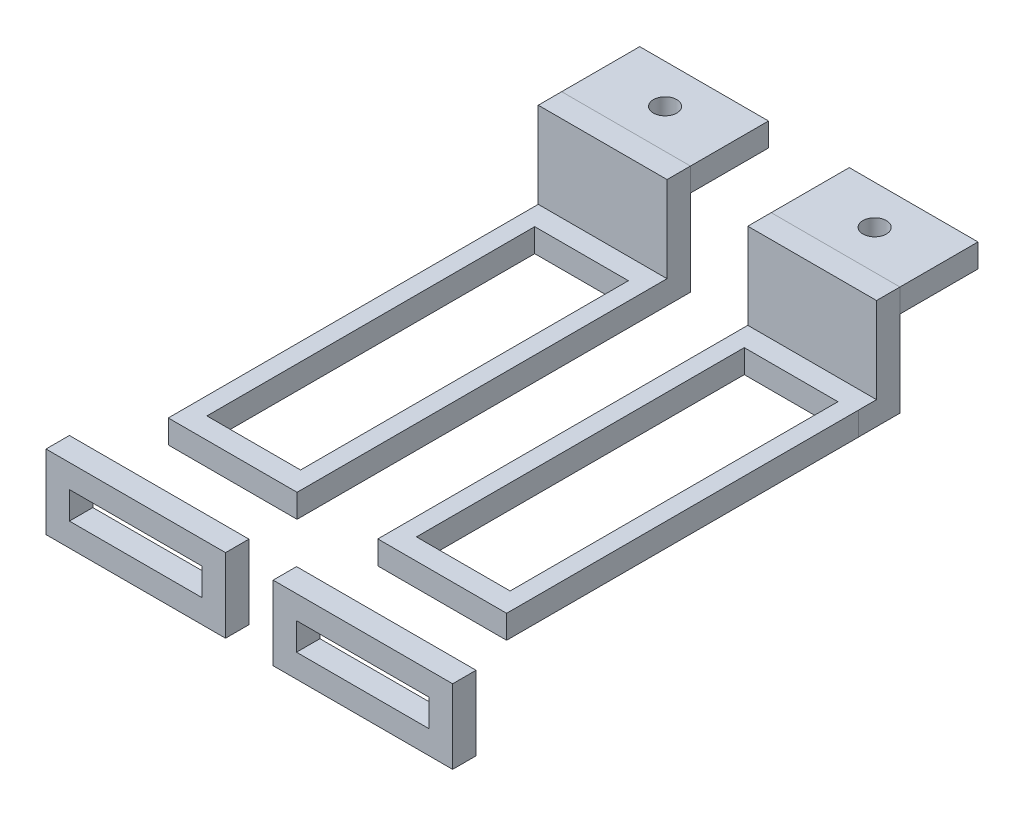
SolidWorks part; units mm, degrees
ref_plane "Front Plane" through (0, 0, 0) normal (0, 0, 1) x (1, 0, 0)
ref_plane "Top Plane" through (0, 0, 0) normal (0, 1, 0) x (1, 0, 0)
ref_plane "Right Plane" through (0, 0, 0) normal (1, 0, 0) x (0, 0, -1)
sketch "Sketch1" plane through (0, 0, 0) normal (0, 0, 1) x (1, 0, 0)
  line L1 (98.6394, -11.1578) -> (-71.3606, -11.1578)
  line L2 (98.6394, -11.1578) -> (98.6394, -8.1578)
  line L3 (98.6394, -8.1578) -> (-71.3606, -8.1578)
  line L4 (-71.3606, -11.1578) -> (-71.3606, -8.1578)
  line L5 (98.6394, -11.1578) -> (-71.3606, -8.1578) construction
  line L6 (98.6394, -8.1578) -> (-71.3606, -11.1578) construction
  point P0 (13.6394, -9.6578)
extrude "Boss-Extrude1" add sketch "Sketch1" along normal blind 10
sketch "Sketch2" plane through (0, -8.1578, 0) normal (0, 1, 0) x (1, 0, 0)
  line L0 (98.6394, -10) -> (-71.3606, -10) construction
  line L1 (-53.3606, -7) -> (-8.0606, -7)
  line L2 (-53.3606, -7) -> (-53.3606, -10)
  line L3 (-53.3606, -10) -> (-8.0606, -10)
  line L4 (-8.0606, -7) -> (-8.0606, -10)
  line L5 (-53.3606, -7) -> (-8.0606, -10) construction
  line L6 (-53.3606, -10) -> (-8.0606, -7) construction
  line L7 (-71.3606, -10) -> (-71.3606, 0) construction
  point P0 (-30.7106, -8.5)
  dimension "D1" = 0
  dimension "D2" = 18
sketch "Sketch4" plane through (0, -8.1578, 0) normal (0, 1, 0) x (1, 0, 0)
  line L0 (-71.3606, -10) -> (-71.3606, 0) construction
  line L1 (98.6394, -10) -> (98.6394, 0) construction
  circle A0 centre (-63.3606, -4.9385) radius 1.2
  circle A1 centre (90.6394, -5.2832) radius 1.2
  dimension "D1" = 8
  dimension "D2" = 8
extrude "Cut-Extrude1" cut sketch "Sketch4" against normal blind 21
extrude "Boss-Extrude6" add sketch "Sketch2" along normal blind 20.3
sketch "Sketch5" plane through (0, 0, 7) normal (0, 0, -1) x (-1, 0, 0)
  line L0 (8.0606, 12.1422) -> (8.0606, -8.1578) construction
  line L1 (53.3606, 12.1422) -> (53.3606, -8.1578) construction
  line L2 (8.0606, 12.1422) -> (53.3606, 12.1422) construction
  line L3 (27.5106, -5.4578) -> (33.9106, -5.4578) construction
  line L4 (27.5106, -3.5578) -> (33.9106, -3.5578)
  line L5 (27.5106, -7.3578) -> (33.9106, -7.3578)
  circle A0 centre (17.4606, 1.9422) radius 8.5
  circle A1 centre (43.9606, 1.9422) radius 8.5
  arc A2 (27.5106, -3.5578) -> (27.5106, -7.3578) centre (27.5106, -5.4578) ccw
  arc A3 (33.9106, -7.3578) -> (33.9106, -3.5578) centre (33.9106, -5.4578) ccw
  point P12 (30.7106, -5.4578)
  dimension "D1" = 26.5
  dimension "D6" = 1.9
  dimension "D2" = 9.4
  dimension "D3" = 9.4
  dimension "D4" = 10.2
  dimension "D5" = 10.2
  dimension "D7" = 6.4
  dimension "D8" = 15.7
  dimension "D9" = 19.45
  dimension "D10" = 19.45
extrude "Cut-Extrude2" cut sketch "Sketch5" against normal blind 20.3
sketch "Sketch6" plane through (0, -8.1578, 0) normal (0, 1, 0) x (1, 0, 0)
  line L0 (98.6394, -10) -> (-8.0606, -10) construction
  line L1 (35.3394, -7) -> (80.6394, -7)
  line L2 (35.3394, -7) -> (35.3394, -10)
  line L3 (35.3394, -10) -> (80.6394, -10)
  line L4 (80.6394, -7) -> (80.6394, -10)
  line L5 (35.3394, -7) -> (80.6394, -10) construction
  line L6 (35.3394, -10) -> (80.6394, -7) construction
  line L7 (98.6394, -10) -> (98.6394, 0) construction
  point P0 (57.9894, -8.5)
  point P9 (80.6394, -8.5)
  dimension "D1" = 0
  dimension "D2" = 18
extrude "Boss-Extrude7" add sketch "Sketch6" along normal blind 20.3
sketch "Sketch7" plane through (0, 0, 10) normal (0, 0, 1) x (1, 0, 0)
  line L0 (35.3394, 12.1422) -> (35.3394, -8.1578) construction
  line L1 (35.3394, 12.1422) -> (80.6394, 12.1422) construction
  line L3 (-33.9106, -7.3578) -> (-27.5106, -7.3578) construction
  line L4 (-71.3606, -11.1578) -> (98.6394, -11.1578) construction
  line L5 (-53.3606, 12.1422) -> (-53.3606, -8.1578) construction
  line L6 (54.8394, -5.4578) -> (61.2394, -5.4578) construction
  line L7 (54.8394, -3.5578) -> (61.2394, -3.5578)
  line L8 (54.8394, -7.3578) -> (61.2394, -7.3578)
  circle A0 centre (44.7394, 1.9422) radius 8.5
  circle A1 centre (71.2394, 1.9422) radius 8.5
  circle A2 centre (-43.9606, 1.9422) radius 8.5 construction
  circle A3 centre (-17.4606, 1.9422) radius 8.5 construction
  arc A5 (-33.9106, -3.5578) -> (-33.9106, -7.3578) centre (-33.9106, -5.4578) ccw construction
  arc A6 (54.8394, -3.5578) -> (54.8394, -7.3578) centre (54.8394, -5.4578) ccw
  arc A7 (61.2394, -7.3578) -> (61.2394, -3.5578) centre (61.2394, -5.4578) ccw
  point P23 (58.0394, -5.4578)
  dimension "D1" = 26.5
  dimension "D6" = 3.8
  dimension "D7" = 19.45
  dimension "D9" = 19.5
  dimension "D10" = 1.9
  dimension "D2" = 26.5
  dimension "D3" = 9.4
  dimension "D4" = 10.2
  dimension "D5" = 10.2
  dimension "D8" = 3.8
extrude "Cut-Extrude3" cut sketch "Sketch7" against normal through all
sketch "Sketch11" plane through (98.6394, 0, 0) normal (1, 0, 0) x (0, 0, -1)
  line L0 (-10, -11.1578) -> (-10, -8.1578) construction
  line L1 (-10, -22.1578) -> (-13, -22.1578)
  line L2 (-10, -22.1578) -> (-10, -8.1578)
  line L3 (-10, -8.1578) -> (-13, -8.1578)
  line L4 (-13, -22.1578) -> (-13, -8.1578)
  line L5 (-10, -22.1578) -> (-13, -8.1578) construction
  line L6 (-10, -8.1578) -> (-13, -22.1578) construction
  line L7 (-10, -8.1578) -> (0, -8.1578) construction
  point P0 (-11.5, -15.1578)
  dimension "D1" = 0
  dimension "D2" = 0
  dimension "D3" = 3
  dimension "D4" = 14
extrude "Boss-Extrude10" add sketch "Sketch11" along normal blind 16.5 separate body
move or copy body "Body-Move/Copy1" bodies to move or copy 125 copy no translate (-106.6404, 0, 0) parameters "D1"=106.6404, "D2"=0, "D3"=0
sketch "Sketch12" plane through (0, 0, 13) normal (0, 0, 1) x (1, 0, 0)
  line L1 (-8.001, -19.1578) -> (8.499, -19.1578)
  line L2 (-8.001, -19.1578) -> (-8.001, -22.1578)
  line L3 (-8.001, -22.1578) -> (8.499, -22.1578)
  line L4 (8.499, -19.1578) -> (8.499, -22.1578)
  line L5 (-8.001, -19.1578) -> (8.499, -22.1578) construction
  line L6 (-8.001, -22.1578) -> (8.499, -19.1578) construction
  point P0 (0.249, -20.6578)
  point P9 (0.7412, -20.8118)
extrude "Boss-Extrude11" add sketch "Sketch12" along normal blind 47.4
sketch "Sketch13" plane through (0, -19.1578, 0) normal (0, 1, 0) x (1, 0, 0)
  line L0 (-8.001, -60.4) -> (-8.001, -13) construction
  line L1 (6.249, -57.7) -> (-5.751, -57.7)
  line L2 (6.249, -57.7) -> (6.249, -15.7)
  line L3 (6.249, -15.7) -> (-5.751, -15.7)
  line L4 (-5.751, -57.7) -> (-5.751, -15.7)
  line L5 (6.249, -57.7) -> (-5.751, -15.7) construction
  line L6 (6.249, -15.7) -> (-5.751, -57.7) construction
  line L7 (8.499, -60.4) -> (-8.001, -60.4) construction
  point P0 (0.249, -36.7)
  dimension "D1" = 2.25
  dimension "D2" = 2.7
extrude "Cut-Extrude5" cut sketch "Sketch13" against normal through all
move or copy body "Body-Move/Copy3" bodies to move or copy 129 copy yes number of copies 1 translate (26.846, 0, 0) parameters "D1"=26.846, "D2"=0, "D3"=0
sketch "Sketch14" plane through (0, -19.1578, 0) normal (0, 1, 0) x (1, 0, 0)
  line L1 (-12.3889, -68.6783) -> (10.6111, -68.6783)
  line L2 (-12.3889, -68.6783) -> (-12.3889, -71.6783)
  line L3 (-12.3889, -71.6783) -> (10.6111, -71.6783)
  line L4 (10.6111, -68.6783) -> (10.6111, -71.6783)
  line L5 (-12.3889, -68.6783) -> (10.6111, -71.6783) construction
  line L6 (-12.3889, -71.6783) -> (10.6111, -68.6783) construction
  point P0 (-0.8889, -70.1783)
extrude "Boss-Extrude12" add sketch "Sketch14" against normal blind 9.5 separate body
sketch "Sketch15" plane through (0, 0, 71.6783) normal (0, 0, 1) x (1, 0, 0)
  line L0 (-12.3889, -19.1578) -> (10.6111, -19.1578) construction
  line L1 (7.6111, -25.6578) -> (-9.3889, -25.6578)
  line L2 (7.6111, -25.6578) -> (7.6111, -22.1578)
  line L3 (7.6111, -22.1578) -> (-9.3889, -22.1578)
  line L4 (-9.3889, -25.6578) -> (-9.3889, -22.1578)
  line L5 (7.6111, -25.6578) -> (-9.3889, -22.1578) construction
  line L6 (7.6111, -22.1578) -> (-9.3889, -25.6578) construction
  line L7 (-12.3889, -28.6578) -> (-12.3889, -19.1578) construction
  point P0 (-0.8889, -23.9078)
  dimension "D1" = 3
  dimension "D2" = 3
extrude "Cut-Extrude6" cut sketch "Sketch15" against normal blind 9.5
move or copy body "Body-Move/Copy4" bodies to move or copy 132 copy yes number of copies 1 translate (29.0983, 0, 0) parameters "D1"=29.0983, "D2"=0, "D3"=0
sketch "Sketch16" plane through (0, -8.1578, 0) normal (0, 1, 0) x (1, 0, 0)
  line L0 (-71.3606, -10) -> (-71.3606, 0) construction
  line L1 (-8.001, -15.1628) -> (-71.3606, -15.1628)
  line L2 (-8.001, -15.1628) -> (-8.001, 5.063)
  line L3 (-8.001, 5.063) -> (-71.3606, 5.063)
  line L4 (-71.3606, -15.1628) -> (-71.3606, 5.063)
  line L5 (-8.001, -15.1628) -> (-71.3606, 5.063) construction
  line L6 (-8.001, 5.063) -> (-71.3606, -15.1628) construction
  line L7 (98.6394, -15.3286) -> (35.3394, -15.3286)
  line L8 (98.6394, -15.3286) -> (98.6394, 8.5445)
  line L9 (98.6394, 8.5445) -> (35.3394, 8.5445)
  line L10 (35.3394, -15.3286) -> (35.3394, 8.5445)
  line L11 (98.6394, -15.3286) -> (35.3394, 8.5445) construction
  line L12 (98.6394, 8.5445) -> (35.3394, -15.3286) construction
  line L13 (-8.001, -10) -> (-8.001, -13) construction
  line L14 (98.6394, -10) -> (98.6394, 0) construction
  line L15 (35.3394, -7) -> (35.3394, -10) construction
  point P0 (-39.6808, -5.0499)
  point P5 (66.9894, -3.3921)
  dimension "D1" = 0
  dimension "D2" = 0
  dimension "D3" = 0
  dimension "D4" = 0
extrude "Cut-Extrude7" cut sketch "Sketch16" against normal through all both and the other way through all
sketch "Sketch17" plane through (0, -8.1578, 0) normal (0, 1, 0) x (1, 0, 0)
  line L0 (35.3394, -10) -> (-8.001, -10) construction
  line L1 (8.499, 9.9659) -> (18.845, 9.9659)
  line L2 (8.499, 9.9659) -> (8.499, -10)
  line L3 (8.499, -10) -> (18.845, -10)
  line L4 (18.845, 9.9659) -> (18.845, -10)
  line L5 (8.499, 9.9659) -> (18.845, -10) construction
  line L6 (8.499, -10) -> (18.845, 9.9659) construction
  line L7 (18.845, -10) -> (18.845, -13) construction
  line L8 (8.499, -10) -> (8.499, -13) construction
  point P0 (13.672, -0.017)
  dimension "D1" = 0
  dimension "D2" = 0
  dimension "D3" = 0
extrude "Cut-Extrude9" cut sketch "Sketch17" against normal through all both and the other way through all
sketch "Sketch18" plane through (0, -8.1578, 0) normal (0, 1, 0) x (1, 0, 0)
  line L0 (-8.001, 0) -> (-8.001, -10) construction
  line L1 (8.499, -10) -> (-8.001, -10) construction
  line L2 (18.845, 0) -> (18.845, -10) construction
  line L3 (35.3394, -10) -> (18.845, -10) construction
  circle A0 centre (0.249, -5) radius 1.5
  circle A1 centre (27.095, -5) radius 1.5
  point P8 (0, 0)
  dimension "D1" = 8.25
  dimension "D2" = 5
  dimension "D3" = 8.25
  dimension "D4" = 5
extrude "Cut-Extrude10" cut sketch "Sketch18" against normal blind 10
